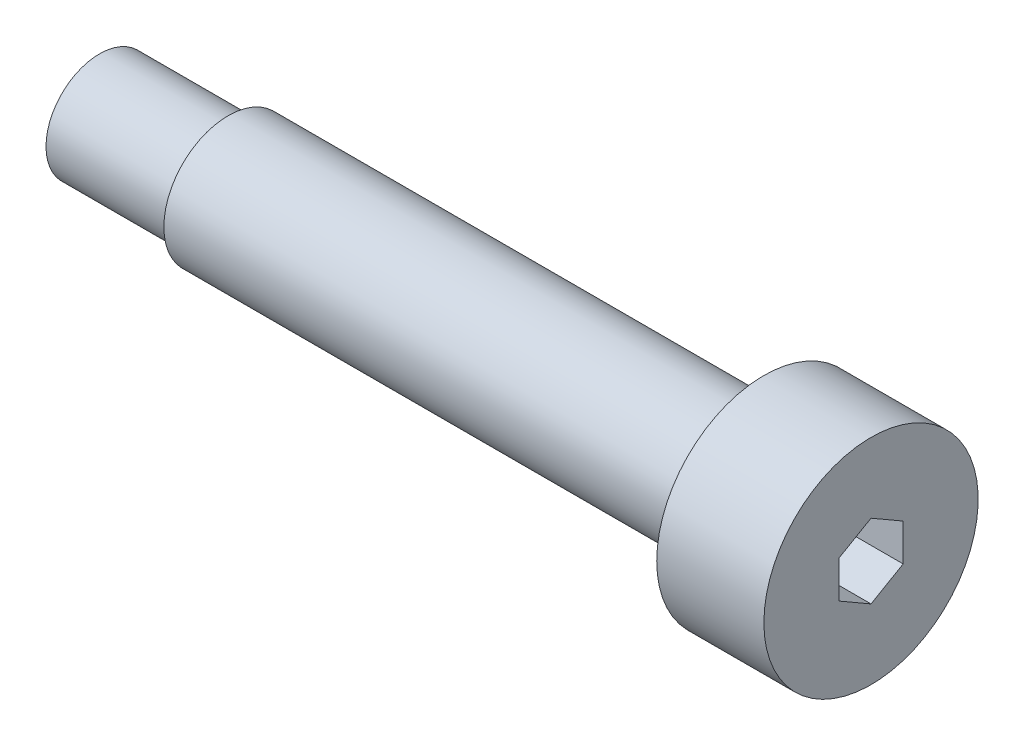
SolidWorks part; units mm, degrees
ref_plane "Front Plane" through (0, 0, 0) normal (0, 0, 1) x (1, 0, 0)
ref_plane "Top Plane" through (0, 0, 0) normal (0, 1, 0) x (1, 0, 0)
ref_plane "Right Plane" through (0, 0, 0) normal (1, 0, 0) x (0, 0, -1)
sketch "Sketch1" plane through (0, 0, 0) normal (0, 0, 1) x (1, 0, 0)
  line L0 (0, 0) -> (104.2442, 0) construction
  line L1 (30, 0) -> (30, 5)
  line L2 (30, 5) -> (25, 5)
  line L3 (25, 5) -> (25, 3)
  line L4 (25, 3) -> (0, 3)
  line L5 (0, 3) -> (0, 2.5)
  line L6 (0, 2.5) -> (-6, 2.5)
  line L7 (-6, 2.5) -> (-6, 0)
  line L8 (-6, 0) -> (30, 0)
  dimension "D_THREAD" = 5
  dimension "L_THREAD" = 6
  dimension "D_SHANK" = 6
  dimension "L_SHANK" = 25
  dimension "L_HEAD" = 5
  dimension "D_HEAD" = 10
revolve "Revolve1" add sketch "Sketch1" angle 360 about L0
cosmetic thread "Cosmetic Thread1"
sketch "Sketch2" plane through (30, 0, 0) normal (1, 0, 0) x (0, 0, -1)
  line L1 (0, 1.7321) -> (-1.5, 0.866)
  line L2 (-1.5, 0.866) -> (-1.5, -0.866)
  line L3 (-1.5, -0.866) -> (0, -1.7321)
  line L4 (0, -1.7321) -> (1.5, -0.866)
  line L5 (1.5, -0.866) -> (1.5, 0.866)
  line L6 (1.5, 0.866) -> (0, 1.7321)
  circle A0 centre (0, 0) radius 1.5 construction
  dimension "D1" = 3
extrude "Cut-Extrude1" cut sketch "Sketch2" against normal blind 3
